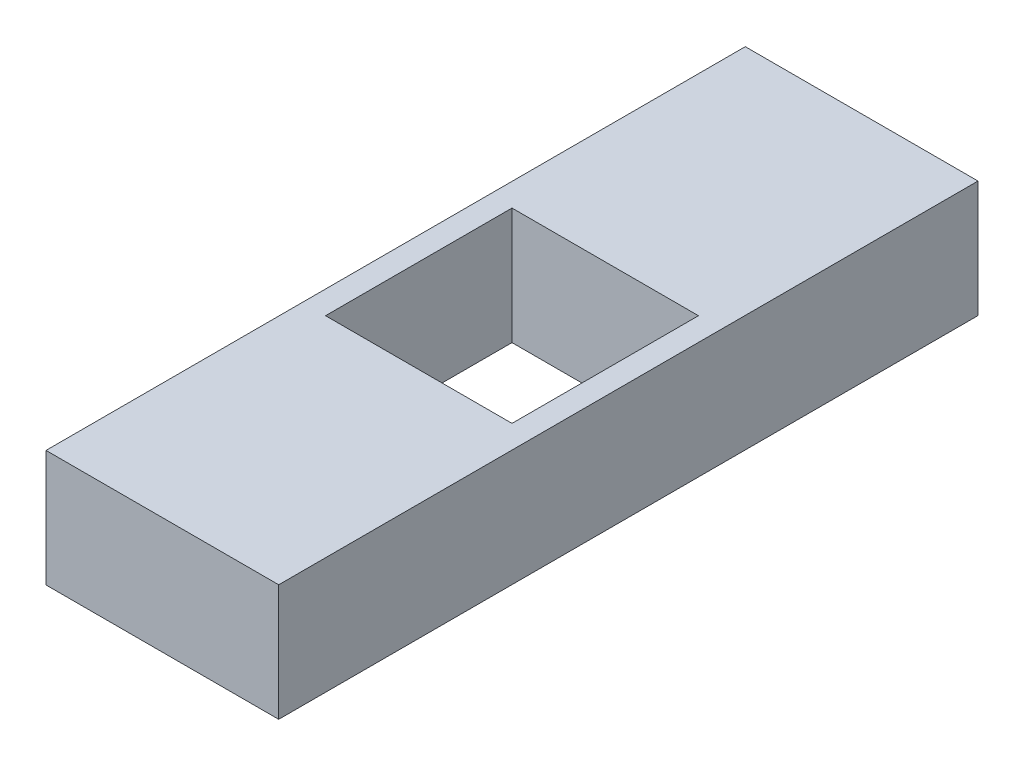
SolidWorks part; units mm, degrees
material "Polyurethane Foam Rigid"
ref_plane "X-Y Datum" through (0, 0, 0) normal (0, 0, 1) x (1, 0, 0)
ref_plane "X-Z Datum" through (0, 0, 0) normal (0, 1, 0) x (1, 0, 0)
ref_plane "Y-Z Datum" through (0, 0, 0) normal (1, 0, 0) x (0, 0, -1)
sketch "Sketch1" plane through (0, 0, 0) normal (0, 0, 1) x (1, 0, 0)
  line L1 (-38.0378, -19.05) -> (38.0378, -19.05)
  line L2 (-38.0378, -19.05) -> (-38.0378, 19.05)
  line L3 (-38.0378, 19.05) -> (38.0378, 19.05)
  line L4 (38.0378, -19.05) -> (38.0378, 19.05)
  line L5 (-38.0378, -19.05) -> (38.0378, 19.05) construction
  line L6 (-38.0378, 19.05) -> (38.0378, -19.05) construction
  point P0 (0, 0)
  dimension "D1" = 38.1
  dimension "D2" = 76.0755
extrude "Boss-Extrude1" add sketch "Sketch1" along normal blind 228.6
sketch "Sketch2" plane through (0, -19.05, 0) normal (0, -1, 0) x (1, 0, 0)
  line L0 (0, 0) -> (0, 228.6) construction
  line L1 (-38.0378, 228.6) -> (38.0378, 228.6) construction
  line L3 (-30.48, 144.78) -> (30.48, 144.78)
  line L4 (-30.48, 144.78) -> (-30.48, 83.82)
  line L5 (-30.48, 83.82) -> (30.48, 83.82)
  line L6 (30.48, 144.78) -> (30.48, 83.82)
  line L7 (-30.48, 144.78) -> (30.48, 83.82) construction
  line L8 (-30.48, 83.82) -> (30.48, 144.78) construction
  point P5 (0, 114.3)
  dimension "D1" = 60.96
  dimension "D2" = 60.96
extrude "Cut-Extrude1" cut sketch "Sketch2" against normal through all
